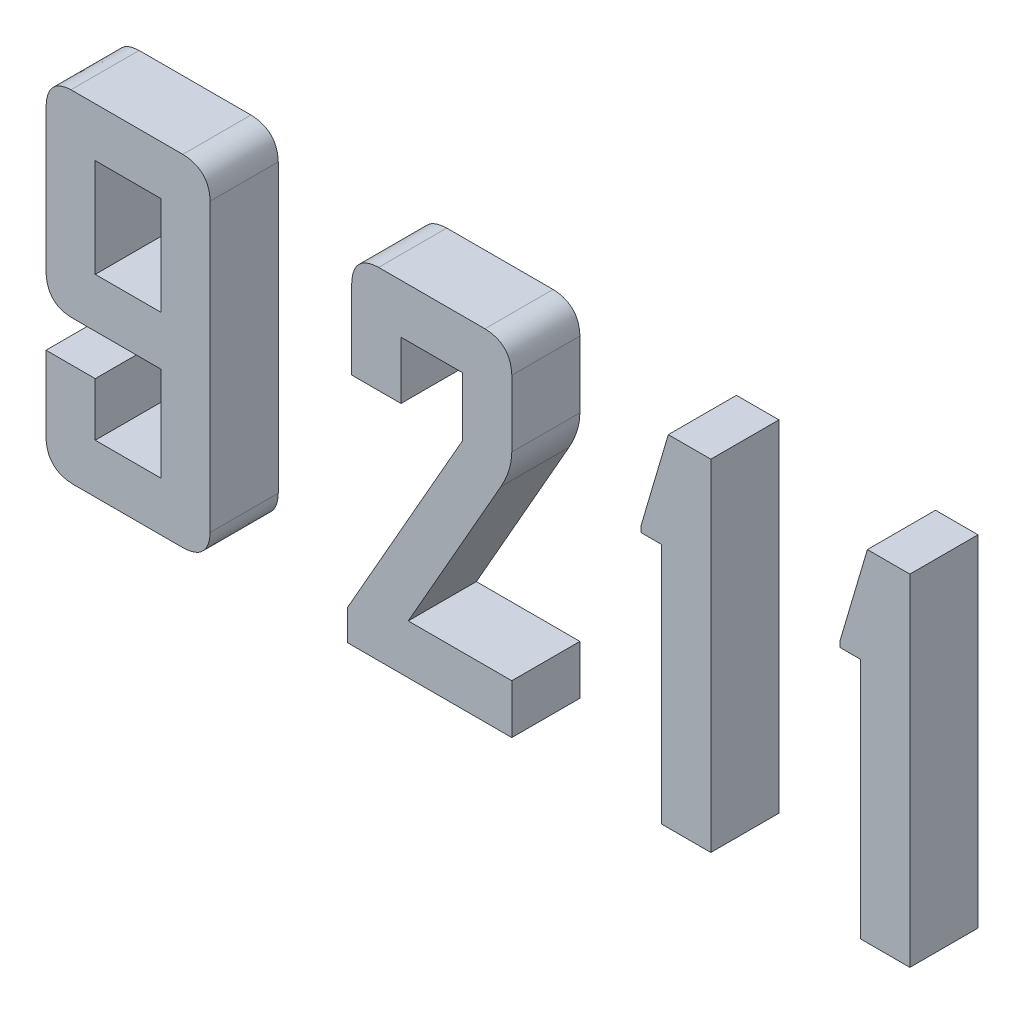
SolidWorks part; units mm, degrees
ref_plane "Front Plane" through (0, 0, 0) normal (0, 0, 1) x (1, 0, 0)
ref_plane "Top Plane" through (0, 0, 0) normal (0, 1, 0) x (1, 0, 0)
ref_plane "Right Plane" through (0, 0, 0) normal (1, 0, 0) x (0, 0, -1)
sketch "Esquisse1" plane through (0, 0, 0) normal (0, 0, 1) x (1, 0, 0)
  line L0 (-24.0302, 0) -> (25.9698, 0) construction
  text T0 "9211" font "Agency FB" height 15
  dimension "D1" = 50
extrude "Boss.-Extru.1" add sketch "Esquisse1" along normal blind 3
